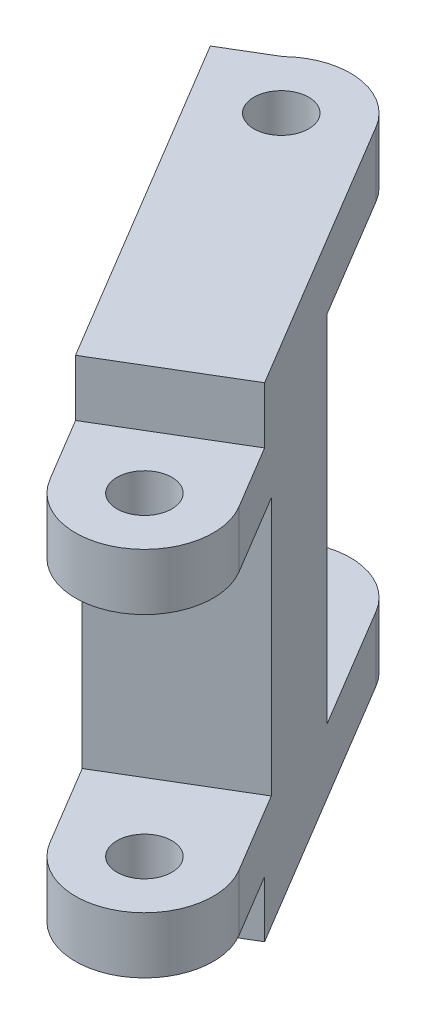
SolidWorks part; units mm, degrees
ref_plane "Front Plane" through (0, 0, 0) normal (0, 0, 1) x (1, 0, 0)
ref_plane "Top Plane" through (0, 0, 0) normal (0, 1, 0) x (1, 0, 0)
ref_plane "Right Plane" through (0, 0, 0) normal (1, 0, 0) x (0, 0, -1)
sketch "Sketch1" plane through (0, 0, 0) normal (0, 1, 0) x (1, 0, 0)
  line L0 (47.2297, 219.0186) -> (732.563, 219.0186) construction
  line L1 (0.5473, 46.7734) -> (-12.0963, 67.9168)
  line L2 (-6.7841, 42.3892) -> (-21.5701, 67.1151)
  line L3 (-21.5701, 67.1151) -> (-18.7462, 68.8038)
  circle A0 centre (-3.1184, 44.5813) radius 1.7
  arc A1 (-6.7841, 42.3892) -> (0.5473, 46.7734) centre (-3.1184, 44.5813) ccw
  circle A2 centre (-15.7738, 65.7176) radius 1.7
  arc A3 (-19.676, 63.9476) -> (-19.1796, 63.1175) centre (-15.7738, 65.7176) ccw
  arc A4 (-12.0963, 67.9168) -> (-18.7462, 68.8038) centre (-15.7738, 65.7176) ccw
extrude "Boss-Extrude1" add sketch "Sketch1" along normal blind 30 contours L1 A4 L3 L2 A1 A0 A2
sketch "Sketch2" plane through (13.6744, 0, -8.1772) normal (-0.8583, 0, 0.5132) x (0.5132, 0, 0.8583)
  line L0 (-68.6721, 30) -> (-68.6721, 0) construction
  line L1 (-68.6721, 4) -> (-55.6721, 4)
  line L2 (-68.6721, 30) -> (-68.6721, 0) construction
  line L3 (-68.6721, 26) -> (-55.6721, 26)
  line L4 (-55.6721, 4) -> (-55.6721, 26)
  line L5 (-39.8624, 30) -> (-68.6721, 30) construction
  line L6 (-39.8624, 0) -> (-68.6721, 0) construction
  line L8 (-55.6721, 26) -> (-75.8056, 26)
  line L9 (-55.6721, 26) -> (-55.6721, 4)
  line L10 (-55.6721, 4) -> (-75.8056, 4)
  line L11 (-75.8056, 26) -> (-75.8056, 4)
  line M8 (-68.6721, 30) -> (-68.6721, 0)
  dimension "D1" = 4
  dimension "D2" = 4
  dimension "D3" = 13
extrude "Cut-Extrude2" cut sketch "Sketch2" against normal blind 30 contours L1 L4 L3 M8 | L8 L11 L10 M8
sketch "Sketch3" plane through (13.6744, 0, -8.1772) normal (-0.8583, 0, 0.5132) x (0.5132, 0, 0.8583)
  line L0 (-55.6721, 4) -> (-55.6721, 26) construction
  line L1 (-45.6721, 7) -> (-29.2785, 7)
  line L2 (-45.6721, 7) -> (-45.6721, 23)
  line L3 (-45.6721, 23) -> (-29.2785, 23)
  line L4 (-29.2785, 7) -> (-29.2785, 23)
  line L5 (-39.8624, 0) -> (-68.6721, 0) construction
  line L6 (-39.8624, 30) -> (-68.6721, 30) construction
  dimension "D1" = 10
  dimension "D2" = 7
  dimension "D3" = 7
extrude "Cut-Extrude3" cut sketch "Sketch3" against normal blind 30
sketch "Sketch5" plane through (0, 0, 0) normal (0, 1, 0) x (1, 0, 0)
  line L0 (-1.4174, 50.9289) -> (-10.2093, 46.073)
  line L1 (-10.2093, 46.073) -> (-5.8134, 38.1137)
  line L2 (-5.8134, 38.1137) -> (3.9724, 43.5184)
  line L3 (3.7771, 43.4105) -> (-1.4174, 50.9289)
sketch "Sketch7" plane through (0, 0, 0) normal (0, -1, 0) x (-1, 0, 0)
  line L0 (1.8178, 50.7284) -> (9.1492, 46.3442)
  line L1 (-0.5473, 46.7734) -> (12.0963, 67.9168) construction
  line L2 (6.7841, 42.3892) -> (21.5701, 67.1151) construction
  line L3 (9.1492, 46.3442) -> (4.2106, 38.0856)
  line L4 (4.2106, 38.0856) -> (-3.391, 42.018)
  line L5 (-3.391, 42.018) -> (1.8178, 50.7284)
extrude "Cut-Extrude4" cut sketch "Sketch7" against normal blind 3.5
sketch "Sketch9" plane through (13.6744, 0, -8.1772) normal (-0.8583, 0, 0.5132) x (0.5132, 0, 0.8583)
  line L0 (-44.4707, 30) -> (-44.4707, 26.5)
  line L1 (-39.8624, 30) -> (-68.6721, 30) construction
  line L2 (-44.4707, 26.5) -> (-33.4167, 26.5)
  line L3 (-33.4167, 26.5) -> (-33.4167, 30.5449)
  line L4 (-33.4167, 30.5449) -> (-44.4707, 30.5449)
  line L5 (-44.4707, 30) -> (-44.4707, 30.5449)
  line L6 (-44.4707, 3.5) -> (-44.4707, 0) construction
  dimension "D1" = 0
  dimension "D2" = 3.5
extrude "Cut-Extrude5" cut sketch "Sketch9" against normal through all
